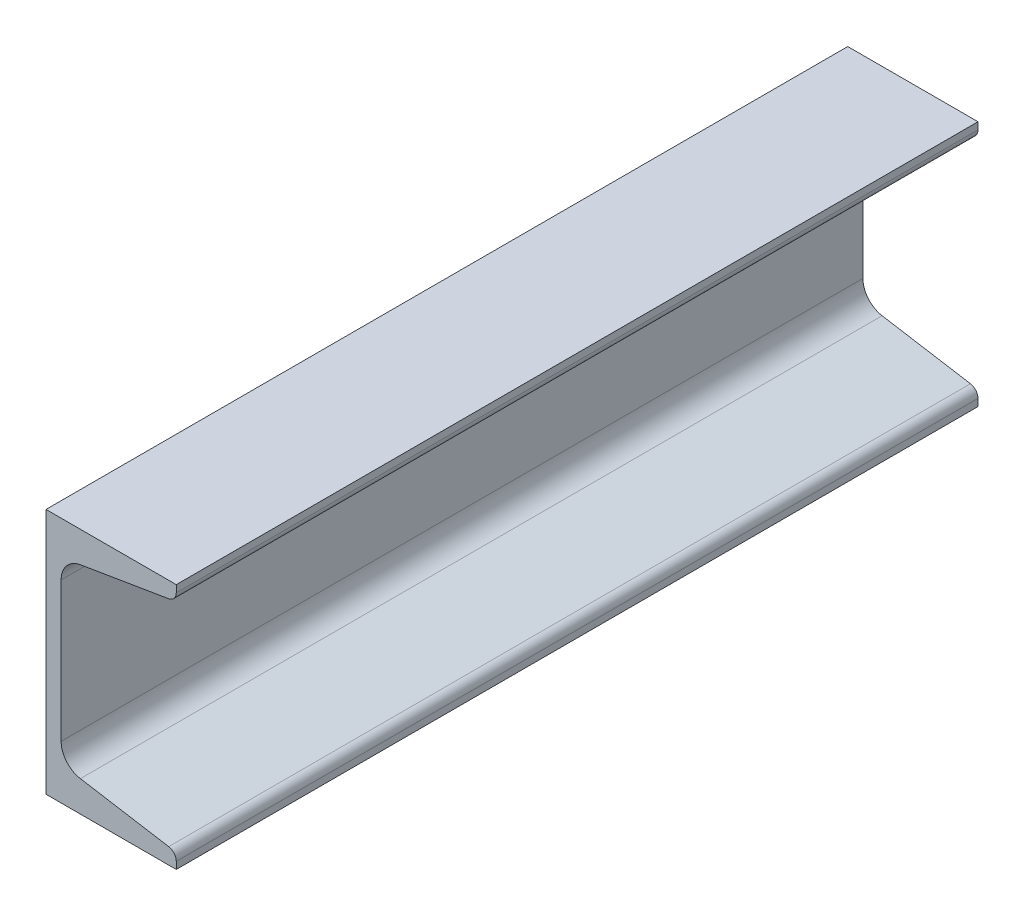
SolidWorks part; units mm, degrees
material "Plain Carbon Steel"
ref_plane "Front Plane" through (0, 0, 0) normal (0, 0, 1) x (1, 0, 0)
ref_plane "Top Plane" through (0, 0, 0) normal (0, 1, 0) x (1, 0, 0)
ref_plane "Right Plane" through (0, 0, 0) normal (1, 0, 0) x (0, 0, -1)
sketch "Sketch1" plane through (0, 0, 0) normal (0, 0, 1) x (1, 0, 0)
  line L0 (0, 0) -> (0, 76.2)
  line L1 (0, 76.2) -> (40.2336, 76.2)
  line L2 (0, 0) -> (40.2336, 0)
  line L12 (4.6736, 59.6934) -> (4.6736, 16.5066)
  line L15 (40.2336, 76.2) -> (40.2336, 74.012)
  line L16 (40.2336, 0) -> (40.2336, 2.188)
  line L17 (10.6163, 66.7086) -> (37.899, 71.256)
  line L18 (10.6163, 9.4914) -> (37.899, 4.944)
  arc A9 (4.6736, 16.5066) -> (10.6163, 9.4914) centre (11.7856, 16.5066) ccw
  arc A10 (4.6736, 59.6934) -> (10.6163, 66.7086) centre (11.7856, 59.6934) cw
  arc A11 (40.2336, 74.012) -> (37.899, 71.256) centre (37.4396, 74.012) cw
  arc A12 (40.2336, 2.188) -> (37.899, 4.944) centre (37.4396, 2.188) ccw
extrude "Boss-Extrude1" add sketch "Sketch1" along normal blind 247.65 contours L0 L1 L15 A11 L17 A10 L12 A9 L18 A12 L16 L2
